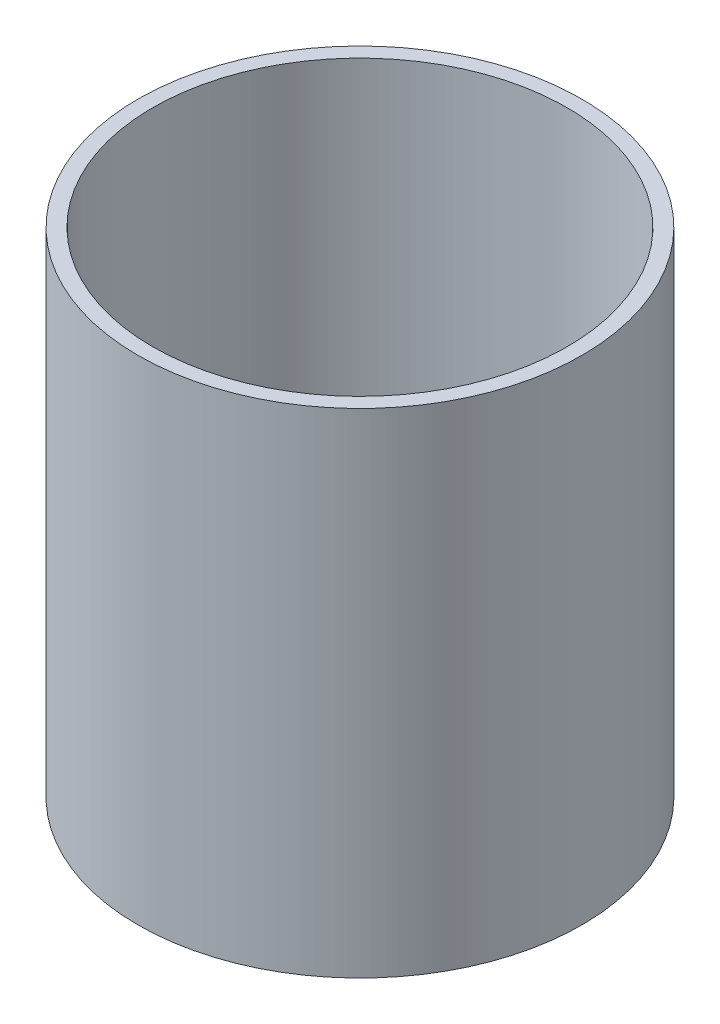
SolidWorks part; units mm, degrees
ref_plane "前视基准面" through (0, 0, 0) normal (0, 0, 1) x (1, 0, 0)
ref_plane "上视基准面" through (0, 0, 0) normal (0, 1, 0) x (1, 0, 0)
ref_plane "右视基准面" through (0, 0, 0) normal (1, 0, 0) x (0, 0, -1)
sketch "草图1" plane through (0, 0, 0) normal (0, 1, 0) x (1, 0, 0)
  circle A0 centre (0, 0) radius 21
  circle A1 centre (0, 0) radius 22.5
  dimension "D1" = 45
  dimension "D2" = 42
extrude "凸台-拉伸1" add sketch "草图1" along normal blind 50
